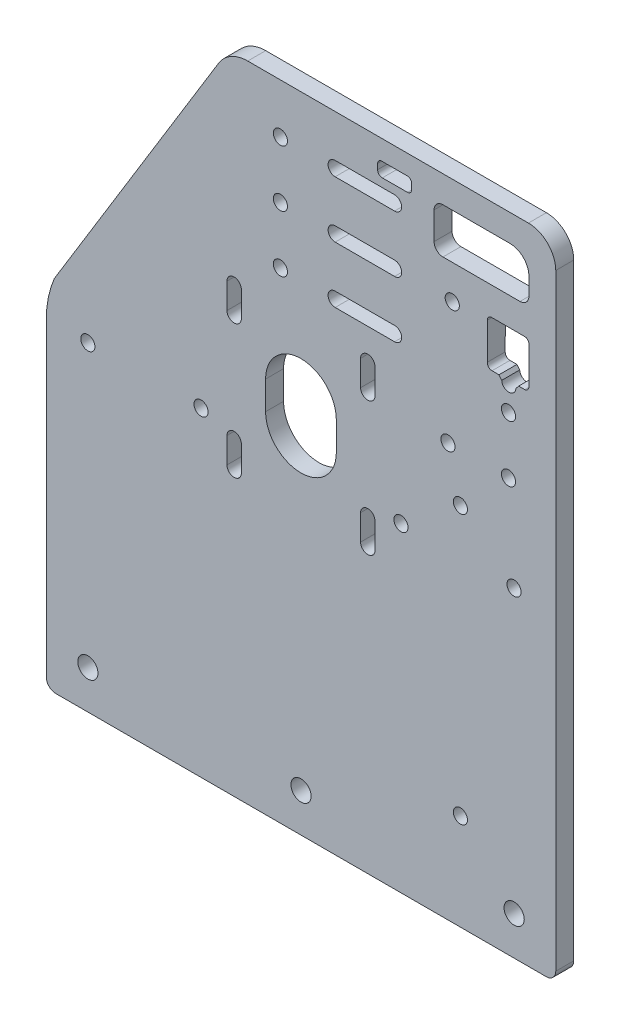
SolidWorks part; units mm, degrees
ref_plane "Front Plane" through (0, 0, 0) normal (0, 0, 1) x (1, 0, 0)
ref_plane "Top Plane" through (0, 0, 0) normal (0, 1, 0) x (1, 0, 0)
ref_plane "Right Plane" through (0, 0, 0) normal (1, 0, 0) x (0, 0, -1)
sketch "Model" plane through (0, 0, 0) normal (0, 0, 1) x (1, 0, 0)
  line L0 (-105.5313, 32.7397) -> (-105.5313, -2.2603) construction
  line L1 (-129.1432, 45.9095) -> (-129.1432, 31.8295) construction
  line L2 (-93.4435, 94.4334) -> (-72.4433, 94.4334)
  line L3 (-79.3794, -12.8744) -> (-79.3794, -3.8744)
  line L4 (-84.4594, -3.8744) -> (-84.4594, -12.8744)
  line L5 (-79.3794, 34.3695) -> (-79.3794, 43.3695)
  line L6 (-84.4594, 43.3695) -> (-84.4594, 34.3695)
  line L15 (-72.4433, 99.4334) -> (-93.4435, 99.4334)
  line L26 (-76.7745, 102.4304) -> (-67.8946, 102.4446)
  line L62 (-38.0223, 62.7815) -> (-35.5523, 62.7831)
  line L63 (-35.5523, 62.7831) -> (-34.5823, 61.5698)
  line L76 (-29.5823, 61.5718) -> (-28.6123, 62.7922)
  line L77 (-28.6123, 62.7922) -> (-26.4266, 62.7958)
  line L88 (-24.9898, 64.3376) -> (-24.9898, 77.5869)
  line L99 (-26.4267, 79.0238) -> (-38.0223, 79.0381)
  line L110 (-39.6854, 77.4136) -> (-39.6913, 64.5554)
  line L122 (-55.3538, 88.9366) -> (-28.1259, 88.9366)
  line L135 (-24.9898, 92.0726) -> (-24.9898, 98.2603)
  line L148 (-31.639, 104.9095) -> (-55.3538, 104.9095)
  line L161 (-58.4898, 101.7734) -> (-58.4898, 92.0726)
  line L184 (-66.4577, 103.8815) -> (-66.4577, 105.9998)
  line L195 (-67.8946, 107.4366) -> (-76.9923, 107.4366)
  line L206 (-78.4292, 105.9998) -> (-78.4435, 104.0993)
  line L213 (-93.4435, 74.4334) -> (-72.4433, 74.4334)
  line L226 (-72.4433, 79.4334) -> (-93.4435, 79.4334)
  line L265 (-93.4435, 54.4335) -> (-72.4433, 54.4335)
  line L278 (-72.4433, 59.4335) -> (-93.4435, 59.4335)
  line L312 (-118.0313, 10.2397) -> (-118.0313, 20.2397)
  line L325 (-93.0313, 20.2397) -> (-93.0313, 10.2397)
  line L350 (-126.6032, 43.3695) -> (-126.6032, 34.3695)
  line L363 (-131.6832, 34.3695) -> (-131.6832, 43.3695)
  line L366 (-131.6832, -12.8744) -> (-131.6832, -3.8744)
  line L379 (-126.6032, -3.8744) -> (-126.6032, -12.8744)
  line L491 (-195.5313, -109.7177) -> (-195.5313, -0.3645)
  line L502 (-192.6798, 13.6861) -> (-134.5879, 108.6679)
  line L515 (-124.3385, 114.4095) -> (-25.1553, 114.4095)
  line L528 (-15.4898, 104.7439) -> (-15.4913, -109.7177)
  line L541 (-18.8541, -113.0804) -> (-192.1685, -113.0804)
  arc A0 (-67.8946, 107.4366) -> (-66.4577, 105.9998) centre (-67.8946, 105.9998) cw
  arc A1 (-67.8946, 102.4446) -> (-66.4577, 103.8815) centre (-67.8946, 103.8815) ccw
  arc A2 (-78.4292, 105.9998) -> (-76.9923, 107.4366) centre (-76.9923, 105.9998) cw
  arc A3 (-78.4435, 104.0993) -> (-76.7745, 102.4304) centre (-76.7772, 104.0966) ccw
  arc A4 (-72.4433, 99.4334) -> (-72.4433, 94.4334) centre (-72.4433, 96.9334) cw
  arc A5 (-93.4435, 99.4334) -> (-93.4435, 94.4334) centre (-93.4435, 96.9334) ccw
  arc A6 (-31.639, 104.9095) -> (-24.9898, 98.2603) centre (-31.639, 98.2603) cw
  arc A7 (-28.1259, 88.9366) -> (-24.9898, 92.0726) centre (-28.1259, 92.0726) ccw
  arc A8 (-58.4898, 92.0726) -> (-55.3538, 88.9366) centre (-55.3538, 92.0726) ccw
  arc A9 (-55.3538, 104.9095) -> (-58.4898, 101.7734) centre (-55.3538, 101.7734) ccw
  arc A10 (-25.1553, 114.4095) -> (-15.4898, 104.7439) centre (-25.1553, 104.7439) cw
  arc A11 (-34.5823, 61.5698) -> (-29.5823, 61.5718) centre (-32.0824, 61.6781) ccw
  arc A12 (-26.4266, 62.7958) -> (-24.9898, 64.3376) centre (-26.5355, 64.3376) ccw
  arc A13 (-39.6913, 64.5554) -> (-38.0223, 62.7815) centre (-38.0233, 64.4526) ccw
  circle A14 centre (-105.5113, -99.4166) radius 3.5687
  circle A15 centre (-30.1913, -99.4166) radius 3.5687
  circle A16 centre (-180.8313, -99.4166) radius 3.5687
  arc A17 (-39.6854, 77.4136) -> (-38.0223, 79.0381) centre (-38.0598, 77.4128) cw
  circle A18 centre (-112.8005, 96.9042) radius 2.5006
  circle A19 centre (-112.8005, 76.9042) radius 2.5006
  circle A20 centre (-112.8005, 56.8745) radius 2.5006
  circle A21 centre (-52.0657, 76.8582) radius 2.5006
  circle A22 centre (-53.5817, 32.8993) radius 2.5006
  circle A23 centre (-49.1913, 15.9519) radius 2.5006
  circle A24 centre (-32.1913, 52.8993) radius 2.5006
  circle A25 centre (-32.1913, 32.8993) radius 2.5006
  circle A26 centre (-30.2365, 0.1639) radius 2.5006
  circle A27 centre (-70.1913, -0.0551) radius 2.5006
  circle A28 centre (-140.8313, -0.0551) radius 2.5006
  circle A29 centre (-180.8313, -0.0551) radius 2.5006
  circle A30 centre (-49.1913, -79.0481) radius 2.5006
  arc A31 (-24.9898, 77.5869) -> (-26.4267, 79.0238) centre (-26.4267, 77.5869) ccw
  arc A32 (-118.0313, 20.2397) -> (-93.0313, 20.2397) centre (-105.5313, 20.2397) cw
  arc A33 (-118.0313, 10.2397) -> (-93.0313, 10.2397) centre (-105.5313, 10.2397) ccw
  arc A34 (-131.6832, 34.3695) -> (-126.6032, 34.3695) centre (-129.1432, 34.3695) ccw
  arc A35 (-131.6832, 43.3695) -> (-126.6032, 43.3695) centre (-129.1432, 43.3695) cw
  arc A36 (-131.6832, -3.8744) -> (-126.6032, -3.8744) centre (-129.1432, -3.8744) cw
  arc A37 (-131.6832, -12.8744) -> (-126.6032, -12.8744) centre (-129.1432, -12.8744) ccw
  arc A38 (-79.3794, -3.8744) -> (-84.4594, -3.8744) centre (-81.9194, -3.8744) ccw
  arc A39 (-79.3794, -12.8744) -> (-84.4594, -12.8744) centre (-81.9194, -12.8744) cw
  arc A40 (-79.3794, 34.3695) -> (-84.4594, 34.3695) centre (-81.9194, 34.3695) cw
  arc A41 (-79.3794, 43.3695) -> (-84.4594, 43.3695) centre (-81.9194, 43.3695) ccw
  arc A42 (-93.4435, 79.4334) -> (-93.4435, 74.4334) centre (-93.4435, 76.9334) ccw
  arc A43 (-72.4433, 79.4334) -> (-72.4433, 74.4334) centre (-72.4433, 76.9334) cw
  arc A44 (-72.4433, 59.4335) -> (-72.4433, 54.4335) centre (-72.4433, 56.9335) cw
  arc A45 (-93.4435, 59.4335) -> (-93.4435, 54.4335) centre (-93.4435, 56.9335) ccw
  arc A46 (-18.8541, -113.0804) -> (-15.4913, -109.7177) centre (-18.8541, -109.7177) ccw
  arc A47 (-195.5313, -109.7177) -> (-192.1685, -113.0804) centre (-192.1685, -109.7177) ccw
  arc A48 (-192.6798, 13.6861) -> (-195.5313, -0.3645) centre (-159.4891, -0.3645) ccw
  arc A49 (-124.3385, 114.4095) -> (-134.5879, 108.6679) centre (-124.3385, 102.3904) ccw
extrude "Boss-Extrude1" add sketch "Model" along normal blind 6.35
